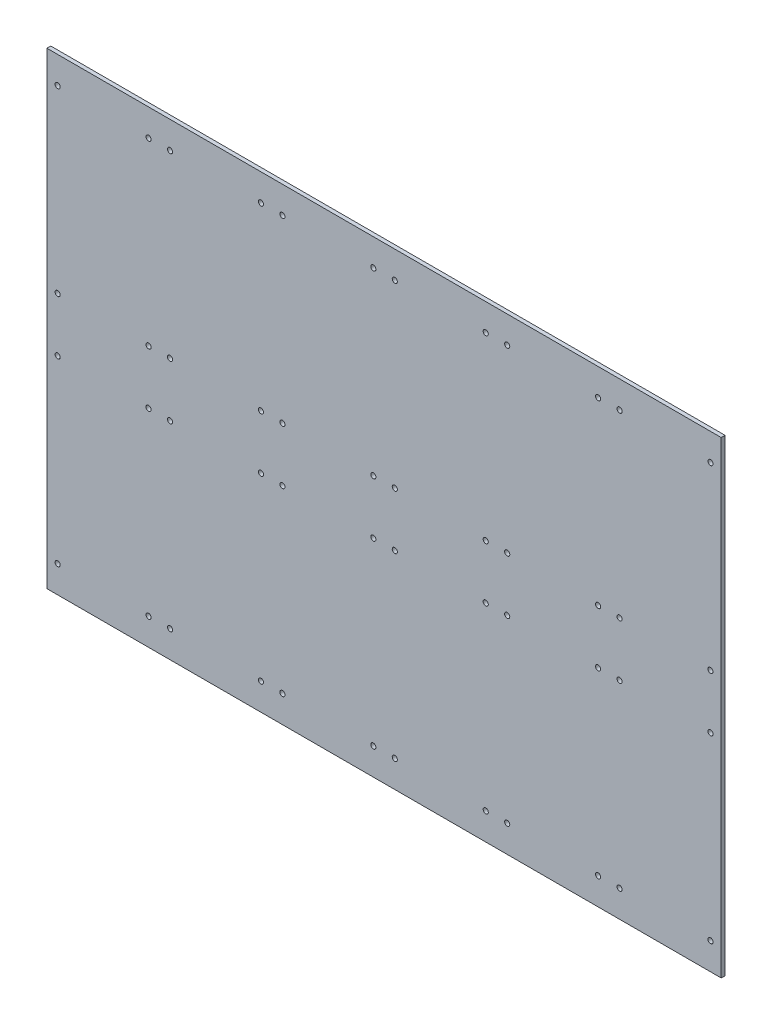
SolidWorks part; units mm, degrees
ref_plane "Front Plane" through (0, 0, 0) normal (0, 0, 1) x (1, 0, 0)
ref_plane "Top Plane" through (0, 0, 0) normal (0, 1, 0) x (1, 0, 0)
ref_plane "Right Plane" through (0, 0, 0) normal (1, 0, 0) x (0, 0, -1)
sketch "Sketch1" plane through (0, 0, 0) normal (0, 0, 1) x (1, 0, 0)
  line L0 (-17.675, 45.5) -> (-17.675, -45.5) construction
  line L1 (-21.85, 45.5) -> (21.85, 45.5)
  line L2 (-21.85, 45.5) -> (-21.85, -45.5)
  line L3 (-21.85, -45.5) -> (21.85, -45.5)
  line L4 (21.85, 45.5) -> (21.85, -45.5)
  line L5 (-21.85, 45.5) -> (21.85, -45.5) construction
  line L6 (-21.85, -45.5) -> (21.85, 45.5) construction
  line L7 (0, 45.5) -> (0, -45.5) construction
  line L8 (17.675, 45.5) -> (17.675, -45.5) construction
  line L9 (-21.85, 0) -> (21.85, 0) construction
  circle A0 centre (-17.675, 35) radius 1
  circle A1 centre (17.675, 35) radius 1
  circle A2 centre (17.675, -35) radius 1
  circle A3 centre (-17.675, -35) radius 1
  point P0 (0, 0)
  dimension "D5" = 2
  dimension "D1" = 91
  dimension "D2" = 43.7
  dimension "D3" = 35.35
  dimension "D4" = 10.5
extrude "Boss-Extrude1" add sketch "Sketch1" along normal blind 1.5
pattern_linear "LPattern1" count 6 spacing 43.7 along (-1, 0, 0) count 2 spacing 91 along (0, 1, 0) of "Boss-Extrude1"
